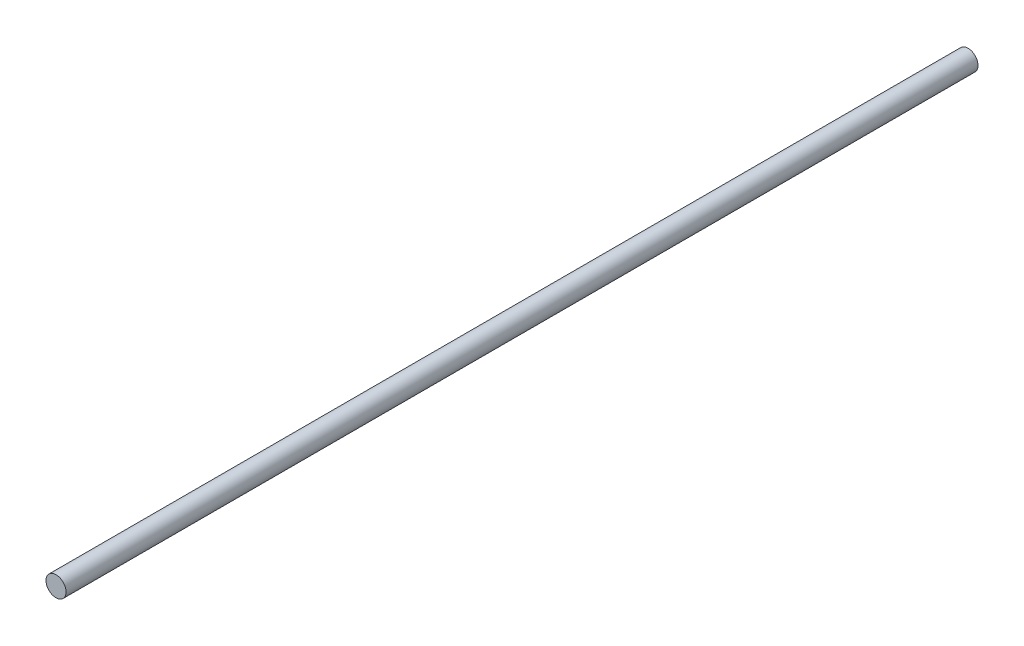
SolidWorks part; units mm, degrees
material "6061-T6 (SS)"
ref_plane "Front Plane" through (0, 0, 0) normal (0, 0, 1) x (1, 0, 0)
ref_plane "Top Plane" through (0, 0, 0) normal (0, 1, 0) x (1, 0, 0)
ref_plane "Right Plane" through (0, 0, 0) normal (1, 0, 0) x (0, 0, -1)
sketch "Sketch1" plane through (0, 0, 0) normal (0, 0, 1) x (1, 0, 0)
  circle A0 centre (0, 0) radius 1.5875
  dimension "D1" = 3.175
extrude "Boss-Extrude1" add sketch "Sketch1" along normal blind 144.4625
